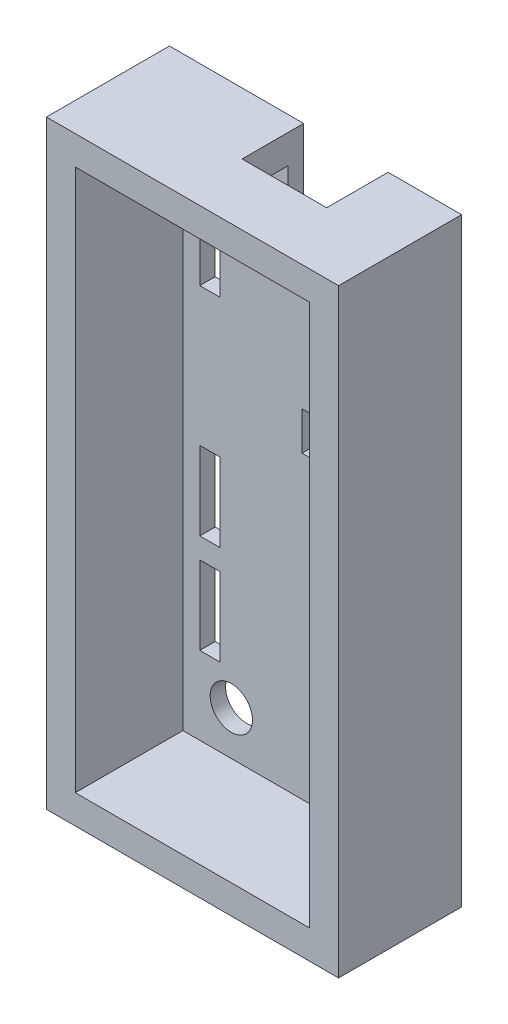
SolidWorks part; units mm, degrees
ref_plane "Front Plane" through (0, 0, 0) normal (0, 0, 1) x (1, 0, 0)
ref_plane "Top Plane" through (0, 0, 0) normal (0, 1, 0) x (1, 0, 0)
ref_plane "Right Plane" through (0, 0, 0) normal (1, 0, 0) x (0, 0, -1)
sketch "Sketch1" plane through (0, 0, 0) normal (0, 0, 1) x (1, 0, 0)
  line L1 (0, 0) -> (38, 0)
  line L2 (0, 0) -> (0, 78)
  line L3 (0, 78) -> (38, 78)
  line L4 (38, 0) -> (38, 78)
  dimension "D1" = 78
  dimension "D2" = 38
extrude "Boss-Extrude1" add sketch "Sketch1" along normal blind 16
sketch "Sketch2" plane through (0, 0, 16) normal (0, 0, 1) x (1, 0, 0)
  line L0 (0, 78) -> (0, 0) construction
  line L1 (3.75, 3.75) -> (34.25, 3.75)
  line L2 (3.75, 3.75) -> (3.75, 74.25)
  line L3 (3.75, 74.25) -> (34.25, 74.25)
  line L4 (34.25, 3.75) -> (34.25, 74.25)
  line L5 (38, 78) -> (0, 78) construction
  dimension "D1" = 30.5
  dimension "D2" = 70.5
  dimension "D3" = 3.75
  dimension "D4" = 3.75
extrude "Cut-Extrude1" cut sketch "Sketch2" against normal blind 14
sketch "Sketch3" plane through (0, 0, 2) normal (0, 0, 1) x (1, 0, 0)
  line L0 (34.25, 74.25) -> (3.75, 74.25) construction
  line L1 (5.95, 69.75) -> (8.55, 69.75)
  line L2 (5.95, 69.75) -> (5.95, 64.63)
  line L3 (5.95, 64.63) -> (8.55, 64.63)
  line L4 (8.55, 69.75) -> (8.55, 64.63)
  line L5 (5.95, 62.63) -> (8.55, 62.63)
  line L6 (5.95, 62.63) -> (5.95, 54.98)
  line L7 (5.95, 54.98) -> (8.55, 54.98)
  line L8 (8.55, 62.63) -> (8.55, 54.98)
  line L9 (5.95, 36.98) -> (8.55, 36.98)
  line L10 (5.95, 36.98) -> (5.95, 26.78)
  line L11 (5.95, 26.78) -> (8.55, 26.78)
  line L12 (8.55, 36.98) -> (8.55, 26.78)
  line L13 (5.95, 24.08) -> (8.55, 24.08)
  line L14 (5.95, 24.08) -> (5.95, 13.88)
  line L15 (5.95, 13.88) -> (8.55, 13.88)
  line L16 (8.55, 24.08) -> (8.55, 13.88)
  line L17 (3.75, 3.75) -> (34.25, 3.75) construction
  line L18 (3.75, 74.25) -> (3.75, 3.75) construction
  line L20 (28.45, 74.25) -> (17.45, 74.25)
  line L21 (28.45, 74.25) -> (28.45, 61.75)
  line L22 (28.45, 61.75) -> (17.45, 61.75)
  line L23 (17.45, 74.25) -> (17.45, 61.75)
  line L24 (30.75, 28.75) -> (20.25, 28.75)
  line L25 (30.75, 28.75) -> (30.75, 14.25)
  line L26 (30.75, 14.25) -> (20.25, 14.25)
  line L27 (20.25, 28.75) -> (20.25, 14.25)
  line L28 (26.25, 47.75) -> (19.25, 47.75)
  line L29 (26.25, 47.75) -> (26.25, 42.75)
  line L30 (26.25, 42.75) -> (19.25, 42.75)
  line L31 (19.25, 47.75) -> (19.25, 42.75)
  circle A0 centre (10.05, 9.45) radius 2.75
  dimension "D13" = 5.5
  dimension "D1" = 5.12
  dimension "D2" = 7.65
  dimension "D3" = 10.2
  dimension "D4" = 10.2
  dimension "D5" = 4.5
  dimension "D6" = 2
  dimension "D7" = 18
  dimension "D8" = 2.7
  dimension "D9" = 5.7
  dimension "D10" = 6.3
  dimension "D11" = 2.2
  dimension "D12" = 2.6
  dimension "D14" = 11
  dimension "D15" = 11.5
  dimension "D16" = 12.5
  dimension "D17" = 14.5
  dimension "D18" = 10.5
  dimension "D19" = 5
  dimension "D20" = 7
  dimension "D21" = 15.5
  dimension "D22" = 26.5
  dimension "D23" = 16.5
  dimension "D24" = 25
extrude "Cut-Extrude2" cut sketch "Sketch3" against normal through all
sketch "Sketch4" plane through (0, 78, 0) normal (0, 1, 0) x (1, 0, 0)
  line L0 (38, 0) -> (0, 0) construction
  line L1 (17.45, 0) -> (28.45, 0)
  line L2 (17.45, 0) -> (17.45, -8)
  line L3 (17.45, -8) -> (28.45, -8)
  line L4 (28.45, 0) -> (28.45, -8)
  line L6 (28.45, 0) -> (28.45, -2) construction
  line L8 (17.45, 0) -> (17.45, -2) construction
  dimension "D1" = 8
extrude "Cut-Extrude3" cut sketch "Sketch4" against normal up to surface (3.75 mm away) up to face at (20.975, 74.25, 5)
